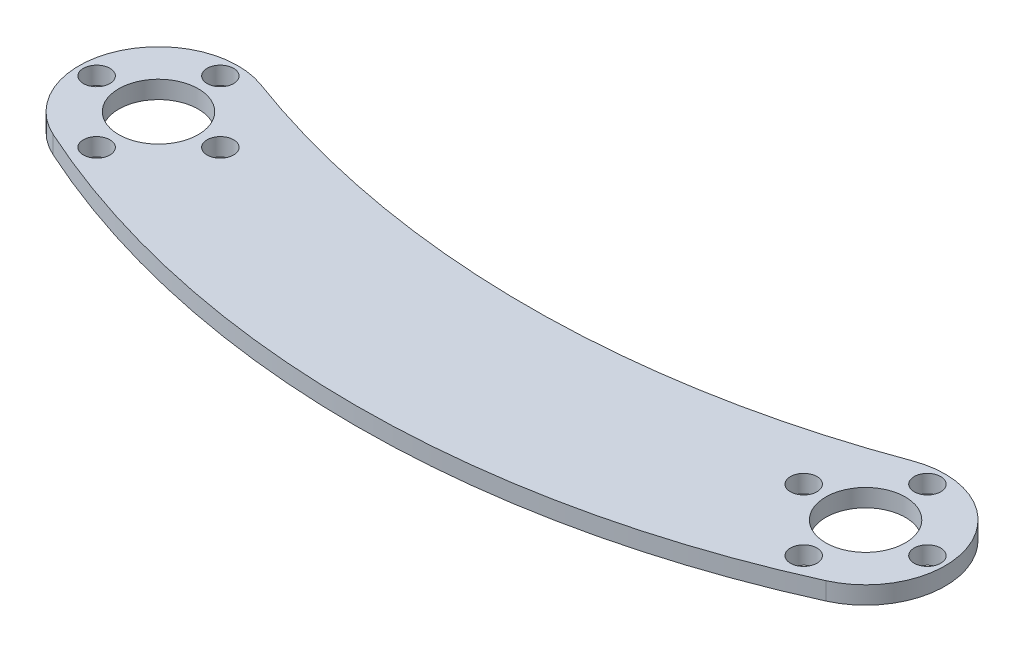
SolidWorks part; units mm, degrees
ref_plane "前视基准面" through (0, 0, 0) normal (0, 0, 1) x (1, 0, 0)
ref_plane "上视基准面" through (0, 0, 0) normal (0, 1, 0) x (1, 0, 0)
ref_plane "右视基准面" through (0, 0, 0) normal (1, 0, 0) x (0, 0, -1)
sketch "草图1" plane through (0, 0, 0) normal (0, 1, 0) x (1, 0, 0)
  line L0 (-11.9008, 0) -> (85.5352, 0) construction
  line L1 (0, 12.8266) -> (0, -10.9886) construction
  line L2 (40, 58.4631) -> (40, -24.6138) construction
  circle A0 centre (0, 0) radius 9 construction
  circle A1 centre (0, 0) radius 7 construction
  circle A2 centre (80, 0) radius 9 construction
  arc A7 (3.1304, 8.438) -> (76.8696, 8.438) centre (40, 107.8193) ccw
  arc A8 (-3.7113, -8.1991) -> (83.7113, -8.1991) centre (40, 88.3685) ccw
  arc A9 (-3.7113, -8.1991) -> (3.1304, 8.438) centre (0, 0) cw
  arc A10 (83.7113, -8.1991) -> (76.8696, 8.438) centre (80, 0) ccw
  dimension "D1" = 18
  dimension "D2" = 14
  dimension "D3" = 18
  dimension "D6" = 106
  dimension "D7" = 106
  dimension "D4" = 80
  dimension "D5" = 40
extrude "凸台-拉伸1" add sketch "草图1" along normal blind 2
sketch "草图2" plane through (0, 2, 0) normal (0, 1, 0) x (1, 0, 0)
  line L0 (-23.5693, 0) -> (97.7625, 0) construction
  line L1 (0, 24.5377) -> (0, -24.5377) construction
  line L2 (80, 22.8254) -> (80, -33.5171) construction
  circle A0 centre (0, 0) radius 4.5
  circle A1 centre (80, 0) radius 4.5
  circle A2 centre (0, 0) radius 7 construction
  circle A3 centre (80, 0) radius 7 construction
  circle A4 centre (7, 0) radius 1.5
  circle A5 centre (0, -7) radius 1.5
  circle A6 centre (-7, 0) radius 1.5
  circle A7 centre (0, 7) radius 1.5
  circle A8 centre (73, 0) radius 1.5
  circle A9 centre (80, 7) radius 1.5
  circle A10 centre (87, 0) radius 1.5
  circle A11 centre (80, -7) radius 1.5
  point P25 (0, 0)
  point P34 (80, 0)
  dimension "D1" = 9
  dimension "D3" = 9
  dimension "D4" = 14
  dimension "D5" = 14
  dimension "D6" = 3
  dimension "D8" = 3
  dimension "D2" = 80
  dimension "D7" = 4
  dimension "D9" = 4
extrude "切除-拉伸1" cut sketch "草图2" against normal through all
